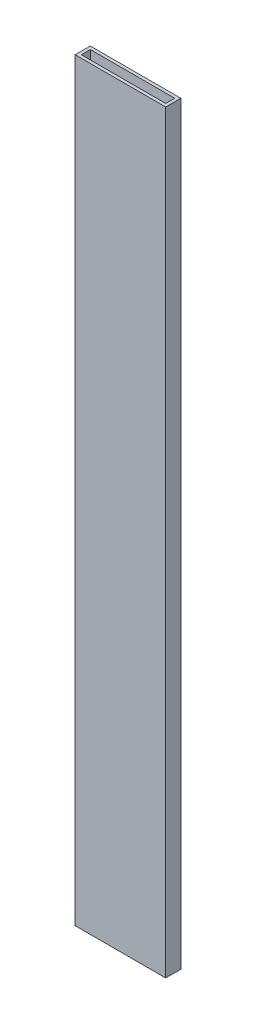
SolidWorks part; units mm, degrees
material "3.1355 (EN-AW 2024)"
ref_plane "Спереди" through (0, 0, 0) normal (0, 0, 1) x (1, 0, 0)
ref_plane "Сверху" through (0, 0, 0) normal (0, 1, 0) x (1, 0, 0)
ref_plane "Справа" through (0, 0, 0) normal (1, 0, 0) x (0, 0, -1)
sketch "Эскиз1" plane through (0, 0, 0) normal (0, 1, 0) x (1, 0, 0)
  line L0 (58, 2) -> (58, 8)
  line L1 (0, 0) -> (60, 0)
  line L2 (0, 0) -> (0, 10)
  line L3 (0, 10) -> (60, 10)
  line L4 (60, 0) -> (60, 10)
  line L5 (2, 8) -> (58, 8)
  line L6 (2, 2) -> (2, 8)
  line L7 (2, 2) -> (58, 2)
  dimension "D1" = 10
  dimension "D2" = 60
  dimension "D3" = 2
extrude "Бобышка-Вытянуть1" add sketch "Эскиз1" along normal blind 500
